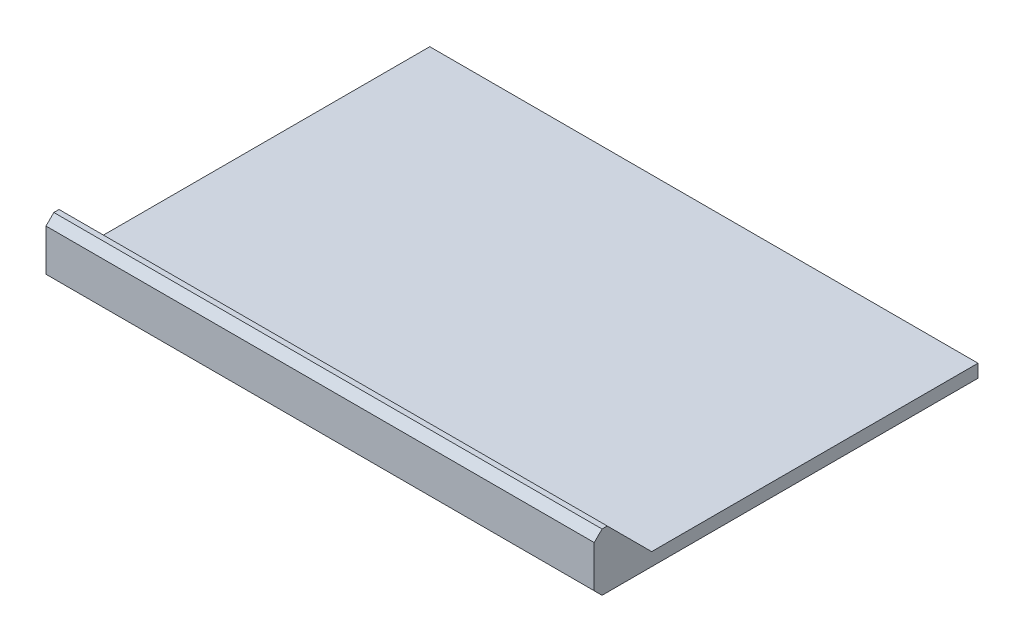
SolidWorks part; units mm, degrees
ref_plane "前视基准面" through (0, 0, 0) normal (0, 0, 1) x (1, 0, 0)
ref_plane "上视基准面" through (0, 0, 0) normal (0, 1, 0) x (1, 0, 0)
ref_plane "右视基准面" through (0, 0, 0) normal (1, 0, 0) x (0, 0, -1)
sketch "草图1" plane through (0, 0, 0) normal (0, 1, 0) x (1, 0, 0)
  line L0 (0, 0) -> (0, 360.68)
  line L1 (0, 360.68) -> (533.4, 360.68)
  line L3 (0, 0) -> (533.4, 0)
  line L4 (533.4, 360.68) -> (533.4, 0)
  dimension "D1" = 533.4
  dimension "D2" = 360.68
extrude "凸台-拉伸1" add sketch "草图1" along normal blind 12.7 contours L3 L4 L1 L0
sketch "草图2" plane through (0, 0, 0) normal (0, 0, 1) x (1, 0, 0)
  line L1 (0, 0) -> (533.4, 0)
  line L2 (0, 0) -> (0, 55.88)
  line L3 (0, 55.88) -> (533.4, 55.88)
  line L4 (533.4, 0) -> (533.4, 55.88)
  line L5 (0, 12.7) -> (0, 0) construction
  point P5 (0, 0)
  point P8 (9.8002, 81.81)
  dimension "D1" = 55.88
extrude "凸台-拉伸2" add sketch "草图2" along normal blind 12.7
chamfer "Chamfer1" distance 7.62 angle 45 2 edges at (266.7, 0, 12.7) (266.7, 55.88, 12.7)
sketch "Sketch1" plane through (533.4, 0, 0) normal (1, 0, 0) x (0, 0, -1)
  line L0 (0, 55.88) -> (0, 12.7)
  line L1 (0, 12.7) -> (43.18, 12.7)
  line L2 (360.68, 12.7) -> (0, 12.7) construction
  line L3 (43.18, 12.7) -> (0, 55.88)
extrude "Extrude1" add sketch "Sketch1" against normal blind 12.7
sketch "Sketch4" plane through (0, 0, 0) normal (-1, 0, 0) x (0, 0, 1)
  line L0 (0, 55.88) -> (0, 12.7)
  line L1 (0, 55.88) -> (0, 12.7) construction
  line L2 (0, 12.7) -> (-43.18, 12.7)
  line L3 (0, 12.7) -> (-360.68, 12.7) construction
  line L4 (-43.18, 12.7) -> (0, 55.88)
  point P9 (0, 0)
extrude "Extrude3" add sketch "Sketch4" against normal blind 12.7 contours L4 L0 L2
